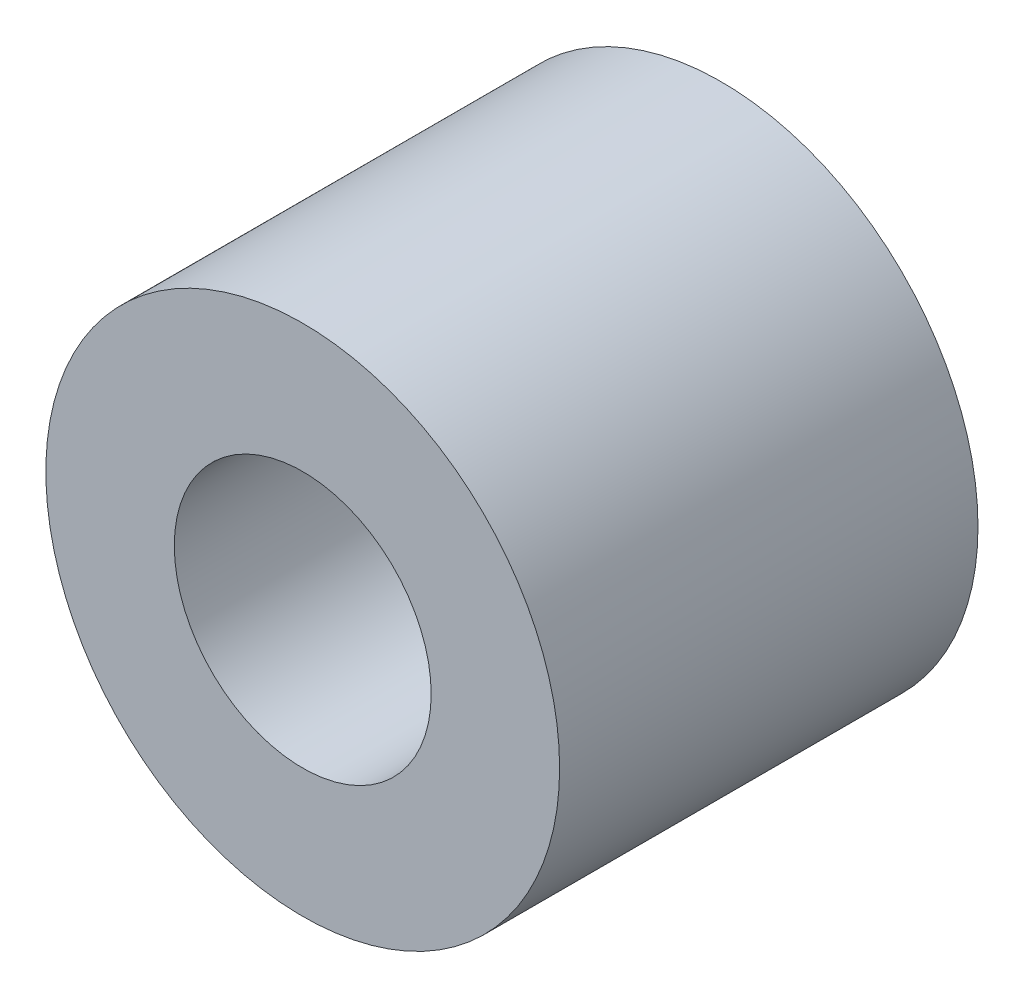
SolidWorks part; units mm, degrees
ref_plane "Plano frontal" through (0, 0, 0) normal (0, 0, 1) x (1, 0, 0)
ref_plane "Plano superior" through (0, 0, 0) normal (0, 1, 0) x (1, 0, 0)
ref_plane "Plano direito" through (0, 0, 0) normal (1, 0, 0) x (0, 0, -1)
sketch "Esboço1" plane through (0, 0, 0) normal (0, 0, 1) x (1, 0, 0)
  circle A0 centre (0, 0) radius 1.75
  circle A1 centre (0, 0) radius 3.5
  dimension "D1" = 3.5
  dimension "D2" = 7
extrude "Ressalto-extrusão1" add sketch "Esboço1" along normal blind 5.7
